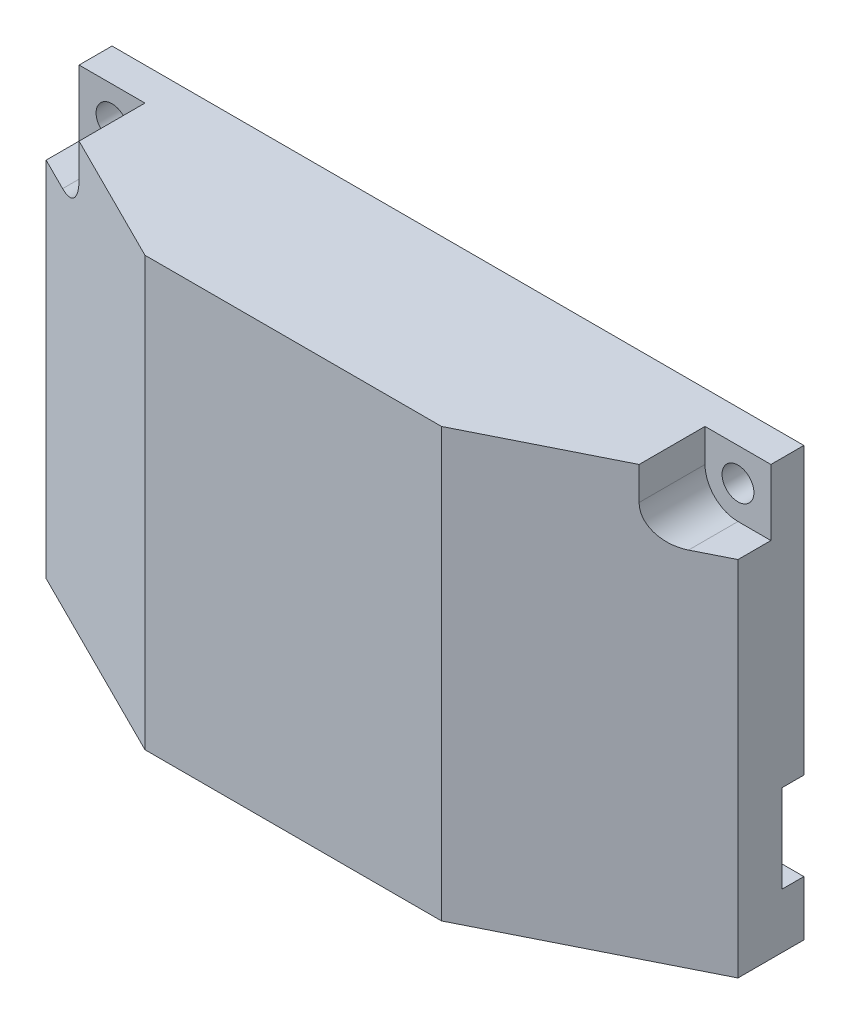
SolidWorks part; units mm, degrees
ref_plane "Alzado" through (0, 0, 0) normal (0, 0, 1) x (1, 0, 0)
ref_plane "Planta" through (0, 0, 0) normal (0, 1, 0) x (1, 0, 0)
ref_plane "Vista lateral" through (0, 0, 0) normal (1, 0, 0) x (0, 0, -1)
sketch "Croquis1" plane through (0, 0, 0) normal (0, 0, 1) x (1, 0, 0)
  line L2 (0, 0) -> (0, 33)
  line L3 (0, 33) -> (63, 33)
  line L4 (63, 0) -> (63, 33)
  line L6 (63, 0) -> (63, -6)
  line L7 (63, -6) -> (0, -6)
  line L8 (0, 0) -> (0, -6)
  dimension "D1" = 63
  dimension "D3" = 6
extrude "Saliente-Extruir1" add sketch "Croquis1" along normal blind 15
sketch "Croquis2" plane through (0, -6, 0) normal (0, -1, 0) x (1, 0, 0)
  line L0 (0, 15) -> (0, 6)
  line L2 (0, 6) -> (18, 15)
  line L4 (18, 15) -> (0, 15)
  line L5 (63, 15) -> (63, 6)
  line L7 (63, 6) -> (45, 15)
  line L8 (45, 15) -> (63, 15)
  dimension "D3" = 27
  dimension "D4" = 18
extrude "Cortar-Extruir1" cut sketch "Croquis2" against normal blind 39 and the other way blind 10
shell "Vaciado1" thickness 2
sketch "Croquis3" plane through (0, 0, 0) normal (0, 0, -1) x (-1, 0, 0)
  line L0 (-63, 33) -> (0, 33) construction
  line L1 (0, 33) -> (0, -6) construction
  line L2 (-63, -6) -> (-63, 33) construction
  line L3 (-63, 30) -> (-63, 27.3542)
  line L9 (-57.1716, 31) -> (-56.127, 31)
  line L11 (-6.873, 31) -> (-5.8284, 31)
  line L13 (-2, 26.127) -> (-2, 27.1716)
  arc A0 (-2, 27.1716) -> (-5.8284, 31) centre (-3, 30) ccw
  arc A1 (-57.1716, 31) -> (-63, 30) centre (-60, 30) ccw
  arc A4 (-63, 27.3542) -> (-56.127, 31) centre (-60, 30) ccw
  arc A6 (-6.873, 31) -> (-2, 26.127) centre (-3, 30) ccw
  dimension "D1" = 6
  dimension "D2" = 6
extrude "Saliente-Extruir2" add sketch "Croquis3" against normal blind 10
sketch "Croquis8" plane through (0, -6, 0) normal (0, -1, 0) x (1, 0, 0)
  line L0 (0, 6) -> (0, 18.6062)
  line L1 (0, 6) -> (18, 15)
  line L2 (18, 15) -> (45, 15)
  line L3 (45, 15) -> (63, 6)
  line L4 (63, 6) -> (63, 18.6062)
  line L5 (63, 18.6062) -> (0, 18.6062)
extrude "Cortar-Extruir2" cut sketch "Croquis8" against normal blind 39
sketch "Croquis9" plane through (0, 0, 0) normal (0, 0, -1) x (-1, 0, 0)
  circle A1 centre (-60, 30) radius 1.45
  circle A2 centre (-3, 30) radius 1.45
  arc A3 (-6.873, 31) -> (-2, 26.127) centre (-3, 30) ccw construction
  arc A4 (-61, 26.127) -> (-56.127, 31) centre (-60, 30) ccw construction
  dimension "D1" = 2.9
  dimension "D2" = 2.9
extrude "Cortar-Extruir3" cut sketch "Croquis9" against normal blind 33
sketch "Croquis10" plane through (0, 0, 15) normal (0, 0, 1) x (1, 0, 0)
  line L0 (6, 30) -> (6, 33)
  line L1 (0, 33) -> (18, 33) construction
  line L2 (6, 33) -> (0, 33)
  line L3 (0, 33) -> (0, 27)
  line L4 (0, 33) -> (0, -6) construction
  line L6 (0, 27) -> (3, 27)
  line L8 (60, 27) -> (63, 27)
  line L10 (63, 27) -> (63, 33)
  line L11 (63, 33) -> (57, 33)
  line L12 (45, 33) -> (63, 33) construction
  line L13 (57, 33) -> (57, 30)
  arc A1 (3, 27) -> (6, 30) centre (3, 30) ccw
  arc A2 (57, 30) -> (60, 27) centre (60, 30) ccw
  dimension "D1" = 6
  dimension "D2" = 6
extrude "Cortar-Extruir4" cut sketch "Croquis10" against normal blind 12
sketch "Croquis11" plane through (0, 0, 0) normal (0, 0, -1) x (-1, 0, 0)
  line L0 (-61, -4) -> (-61, 26.127) construction
  line L1 (-61, -1) -> (-63, -1)
  line L2 (-61, -1) -> (-61, 7)
  line L3 (-61, 7) -> (-63, 7)
  line L4 (-63, -1) -> (-63, 7)
  line L5 (0, -6) -> (-63, -6) construction
  dimension "D1" = 5
  dimension "D2" = 8
extrude "Cortar-Extruir5" cut sketch "Croquis11" against normal blind 2
sketch "Croquis14" plane through (0, -6, 0) normal (0, -1, 0) x (1, 0, 0)
  circle A0 centre (31.5, 12) radius 3
  dimension "D1" = 6
extrude "Saliente-Extruir3" add sketch "Croquis14" against normal blind 8
sketch "Croquis15" plane through (0, 2, 0) normal (0, 1, 0) x (1, 0, 0)
  circle A0 centre (31.5, -12) radius 1.45
  dimension "D1" = 2.9
extrude "Cortar-Extruir6" cut sketch "Croquis15" against normal blind 8 contours A0
